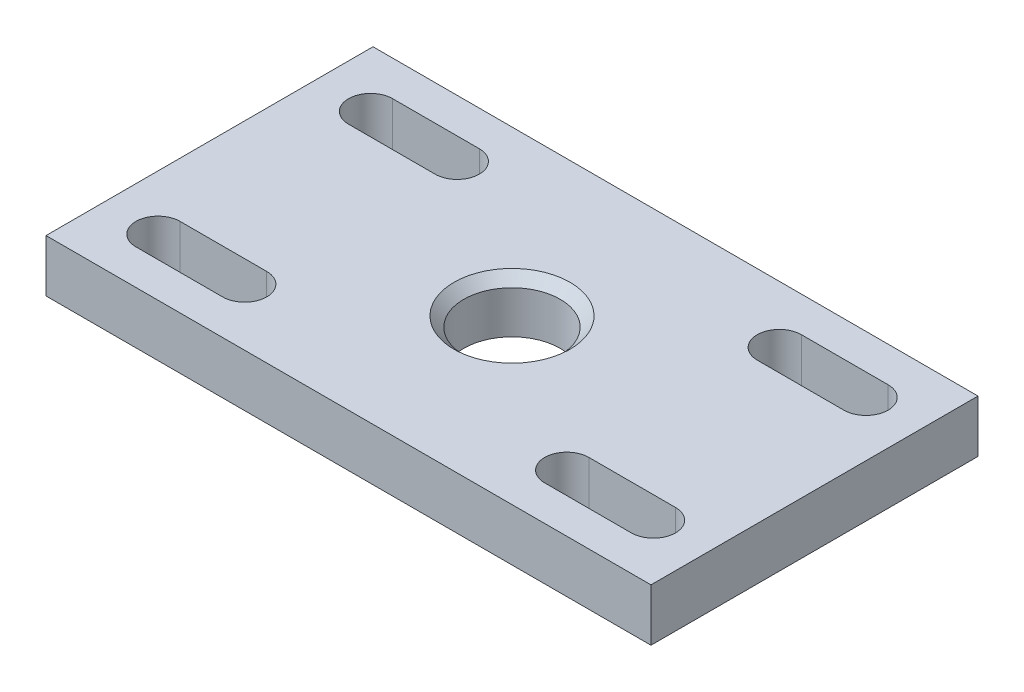
SolidWorks part; units mm, degrees
ref_plane "Front Plane" through (0, 0, 0) normal (0, 0, 1) x (1, 0, 0)
ref_plane "Top Plane" through (0, 0, 0) normal (0, 1, 0) x (1, 0, 0)
ref_plane "Right Plane" through (0, 0, 0) normal (1, 0, 0) x (0, 0, -1)
sketch "Sketch1" plane through (0, 0, 0) normal (0, 1, 0) x (1, 0, 0)
  line L1 (-92.5, -50) -> (92.5, -50)
  line L2 (-92.5, -50) -> (-92.5, 50)
  line L3 (-92.5, 50) -> (92.5, 50)
  line L4 (92.5, -50) -> (92.5, 50)
  line L5 (-92.5, -50) -> (92.5, 50) construction
  line L6 (-92.5, 50) -> (92.5, -50) construction
  point P0 (0, 0)
  dimension "D1" = 100
  dimension "D2" = 185
extrude "Boss-Extrude1" add sketch "Sketch1" along normal blind 16
sketch "Sketch2" plane through (0, 16, 0) normal (0, 1, 0) x (1, 0, 0)
  line L0 (-75.75, 32.5) -> (-49.25, 32.5) construction
  line L1 (-75.75, 39.25) -> (-49.25, 39.25)
  line L2 (-75.75, 25.75) -> (-49.25, 25.75)
  line L3 (-49.25, -32.5) -> (-75.75, -32.5) construction
  line L4 (-49.25, -39.25) -> (-75.75, -39.25)
  line L5 (-49.25, -25.75) -> (-75.75, -25.75)
  line L6 (49.25, 32.5) -> (75.75, 32.5) construction
  line L7 (49.25, 39.25) -> (75.75, 39.25)
  line L8 (49.25, 25.75) -> (75.75, 25.75)
  line L9 (49.25, -32.5) -> (75.75, -32.5) construction
  line L10 (49.25, -25.75) -> (75.75, -25.75)
  line L11 (49.25, -39.25) -> (75.75, -39.25)
  line L12 (-92.5, 50) -> (-92.5, -50) construction
  line L13 (92.5, -50) -> (92.5, 50) construction
  line L15 (92.5, 50) -> (-92.5, 50) construction
  arc A0 (-75.75, 39.25) -> (-75.75, 25.75) centre (-75.75, 32.5) ccw
  arc A1 (-49.25, 25.75) -> (-49.25, 39.25) centre (-49.25, 32.5) ccw
  arc A2 (-49.25, -39.25) -> (-49.25, -25.75) centre (-49.25, -32.5) ccw
  arc A3 (-75.75, -25.75) -> (-75.75, -39.25) centre (-75.75, -32.5) ccw
  arc A4 (49.25, 39.25) -> (49.25, 25.75) centre (49.25, 32.5) ccw
  arc A5 (75.75, 25.75) -> (75.75, 39.25) centre (75.75, 32.5) ccw
  arc A6 (49.25, -25.75) -> (49.25, -39.25) centre (49.25, -32.5) ccw
  arc A7 (75.75, -39.25) -> (75.75, -25.75) centre (75.75, -32.5) ccw
  point P2 (-62.5, 32.5)
  point P7 (-62.5, -32.5)
  point P14 (62.5, 32.5)
  point P21 (62.5, -32.5)
  point P28 (-82.5, 32.5)
  point P29 (-42.5, 32.5)
  dimension "D1" = 13.5
  dimension "D2" = 40
  dimension "D3" = 10
  dimension "D4" = 30
  dimension "D5" = 65
  dimension "D6" = 17.5
extrude "Cut-Extrude1" cut sketch "Sketch2" against normal through all both and the other way through all
hole_wizard "Ø1.0mm Dowel Hole1" positions "Sketch4" profile "Sketch5" hole size "Ø1.0" standard "ISO" end condition up to next
sketch "Sketch4" plane through (0, 16, 0) normal (0, 1, 0) x (1, 0, 0)
  point P0 (0, 0)
sketch "Sketch5" plane through (0, 16, 0) normal (1, 0, 0) x (0, 0, 1)
  line L0 (0, 0) -> (0, 16)
  line L1 (0, 16) -> (14.75, 16)
  line L2 (14.75, 16) -> (14.75, 0)
  line L5 (14.75, 0) -> (0, 0)
  line L11 (0, -6.35) -> (0, 107.95) construction
  dimension "Thru Hole Dia." = 29.5
  dimension "Thru Hole Depth" = 16
chamfer "Chamfer1" distance 3 angle 45 1 edges at (0, 16, 14.75)
